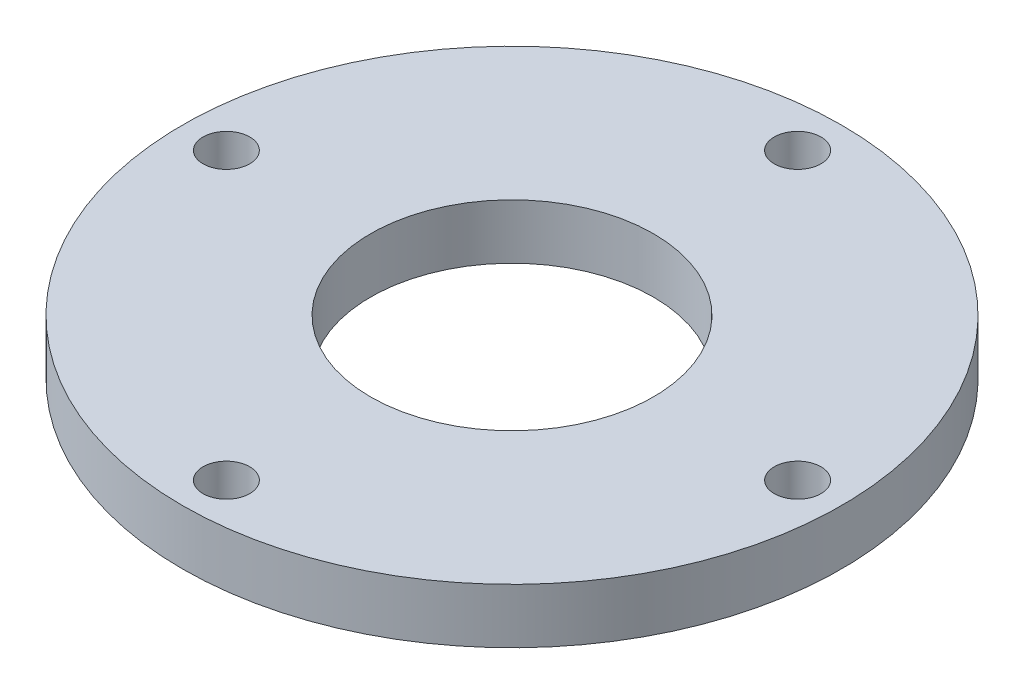
SolidWorks part; units mm, degrees
material "6061-T6 (SS)"
ref_plane "Front Plane" through (0, 0, 0) normal (0, 0, 1) x (1, 0, 0)
ref_plane "Top Plane" through (0, 0, 0) normal (0, 1, 0) x (1, 0, 0)
ref_plane "Right Plane" through (0, 0, 0) normal (1, 0, 0) x (0, 0, -1)
sketch "Sketch1" plane through (0, 0, 0) normal (0, 1, 0) x (1, 0, 0)
  circle A0 centre (0, 0) radius 24
  circle A1 centre (0, 0) radius 10.3
  dimension "D1" = 48
  dimension "D2" = 20.6
extrude "Boss-Extrude1" add sketch "Sketch1" along normal blind 4
sketch "Sketch3" plane through (0, 4, 0) normal (0, 1, 0) x (1, 0, 0)
  circle A0 centre (0, 0) radius 20.8 construction
  circle A1 centre (-20.8, 0) radius 1.7
  circle A2 centre (0, 20.8) radius 1.7
  circle A3 centre (0, 0) radius 20.8 construction
  circle A4 centre (20.8, 0) radius 1.7
  circle A5 centre (0, 0) radius 20.8 construction
  circle A6 centre (0, -20.8) radius 1.7
  circle A7 centre (0, 0) radius 20.8 construction
  point P16 (0, 0)
  dimension "D1" = 41.6
  dimension "D2" = 3.4
  dimension "D3" = 4
extrude "Cut-Extrude1" cut sketch "Sketch3" against normal through all
equation "\"D1@Sketch1\"=\"HUB_LowerRetainerCaptureOD\""
equation "\"D2@Sketch1\"=\"HUB_LowerRetainerCenterHoleDia\""
equation "\"D1@Boss-Extrude1\"=\"HUB_LowerRetainerThk\""
equation "\"D1@Sketch3\"=\"HUB_RetainerBCDia\""
equation "\"D2@Sketch3\"=\"HUB_RetainerClearDia\""
equation "\"____ VERSION / MIRROR CONTROL ____\" = 0"
equation "\"SYS_VersionTag\" = 2.00"
equation "\"____ BEARING BLOCK ____\" = 0"
equation "\"BRG_BearingOD\" = 22mm"
equation "\"____ HUB SEATS + BRIDGE ____\" = 0"
equation "\"HUB_MainBodyOD\" = 48mm"
equation "\"____ HUB RETAINERS + DECK INTERFACE ____\" = 0"
equation "\"HUB_RetainerScrewSize\" = 3mm"
equation "\"HUB_RetainerScrewCount\" = 4"
equation "\"HUB_RetainerClearDia\" = 3.4mm"
equation "\"HUB_RetainerEdgeMin\" = 1.5mm"
equation "\"HUB_RetainerBoltR\" = (\"HUB_MainBodyOD\" / 2) - (\"HUB_RetainerClearDia\" / 2) - \"HUB_RetainerEdgeMin\""
equation "\"HUB_RetainerBCDia\" = 2*\"HUB_RetainerBoltR\""
equation "\"____ HUB RETAINER THREAD / BLIND-HOLE MACHINING INTENT ____\" = 0"
equation "\"HUB_RetainerThreadEngagementMin\" = 3.0mm"
equation "\"HUB_RetainerThreadEngagementTarget\" = 4.5mm"
equation "\"HUB_RetainerScrewIntoHubTarget\" = \"HUB_RetainerThreadEngagementTarget\""
equation "\"HUB_RetainerScrewIntoHubMin\" = \"HUB_RetainerThreadEngagementMin\""
equation "\"HUB_LowerRetainerCaptureThk\" = 4.0mm"
equation "\"HUB_LowerRetainerCaptureOD\" = \"HUB_MainBodyOD\""
equation "\"HUB_LowerRetainerCenterClearDia\" = 20.6mm"
equation "\"____ HUB VARIABLE COMPATIBILITY ALIASES (KEEP v2.00 MAP STABLE) ____\" = 0"
equation "\"HUB_LowerRetainerThk\" = \"HUB_LowerRetainerCaptureThk\""
equation "\"HUB_LowerRetainerOD\" = \"HUB_LowerRetainerCaptureOD\""
equation "\"HUB_LowerRetainerCenterHoleDia\" = \"HUB_LowerRetainerCenterClearDia\""
equation "\"____ GENERATED EXPORTS ____\" = 0"
equation "\"LBR_MinScrewReach\" = \"HUB_LowerRetainerThk\" + \"HUB_RetainerScrewIntoHubMin\""
equation "\"LBR_RecommendedScrewReach\" = \"HUB_LowerRetainerThk\" + \"HUB_RetainerScrewIntoHubTarget\""
